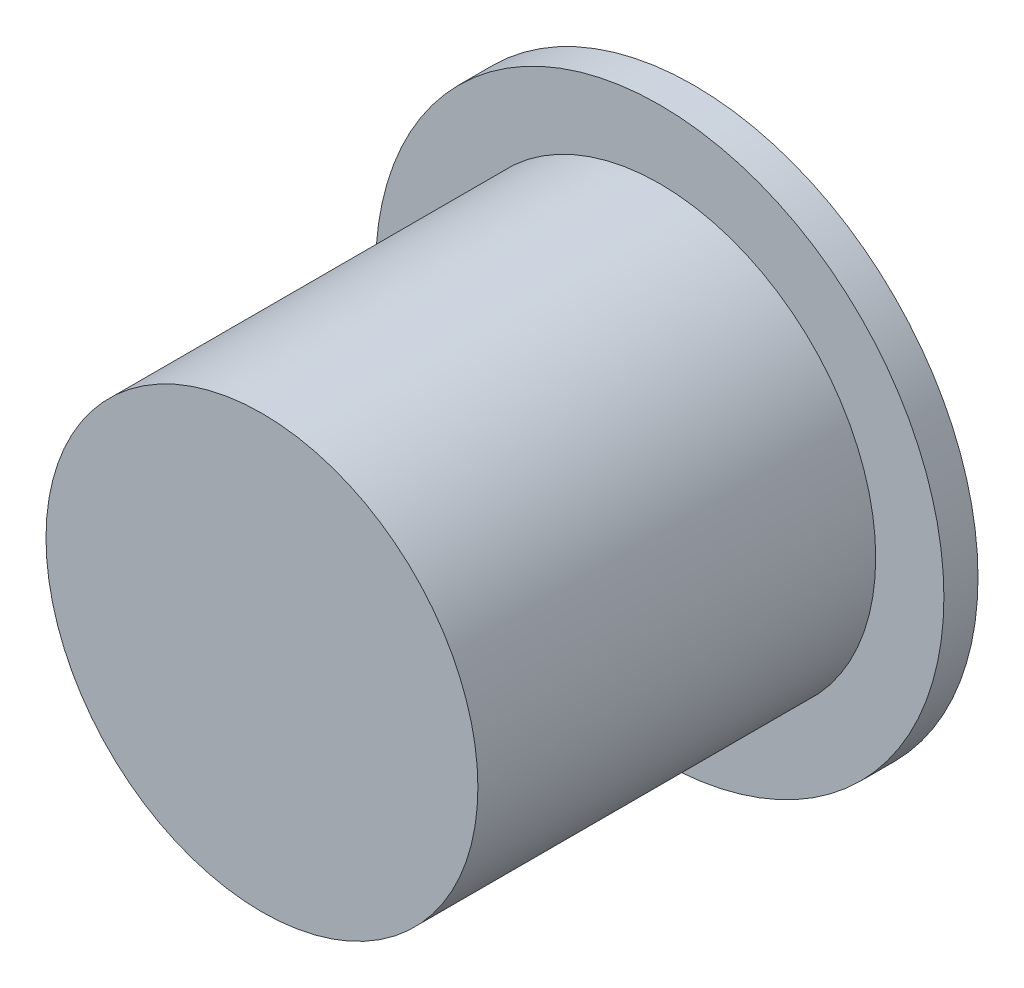
SolidWorks part; units mm, degrees
ref_plane "Plan1" through (0, 0, 0) normal (0, 0, 1) x (1, 0, 0)
ref_plane "Plan2" through (0, 0, 0) normal (0, 1, 0) x (1, 0, 0)
ref_plane "Plan3" through (0, 0, 0) normal (1, 0, 0) x (0, 0, -1)
sketch "Esquisse1" plane through (0, 0, 0) normal (0, 0, 1) x (1, 0, 0)
  circle A0 centre (0, 0) radius 19
  dimension "D1" = 38
extrude "Base-Extrusion" add sketch "Esquisse1" along normal blind 35
sketch "Esquisse2" plane through (0, 0, 0) normal (0, 0, -1) x (-1, 0, 0)
  circle A0 centre (0, 0) radius 25
  dimension "D1" = 50
extrude "Boss.-Extru.1" add sketch "Esquisse2" along normal blind 3
sketch "Esquisse3" plane through (0, 0, -3) normal (0, 0, -1) x (-1, 0, 0)
  circle A0 centre (0, 0) radius 10
  dimension "D1" = 20
extrude "Boss.-Extru.2" add sketch "Esquisse3" along normal blind 2
sketch "Esquisse4" plane through (0, 0, -5) normal (0, 0, -1) x (-1, 0, 0)
  circle A0 centre (0, 0) radius 2.5
  dimension "D1" = 5
extrude "Enlèv. mat.-Extru.1" cut sketch "Esquisse4" against normal blind 10
